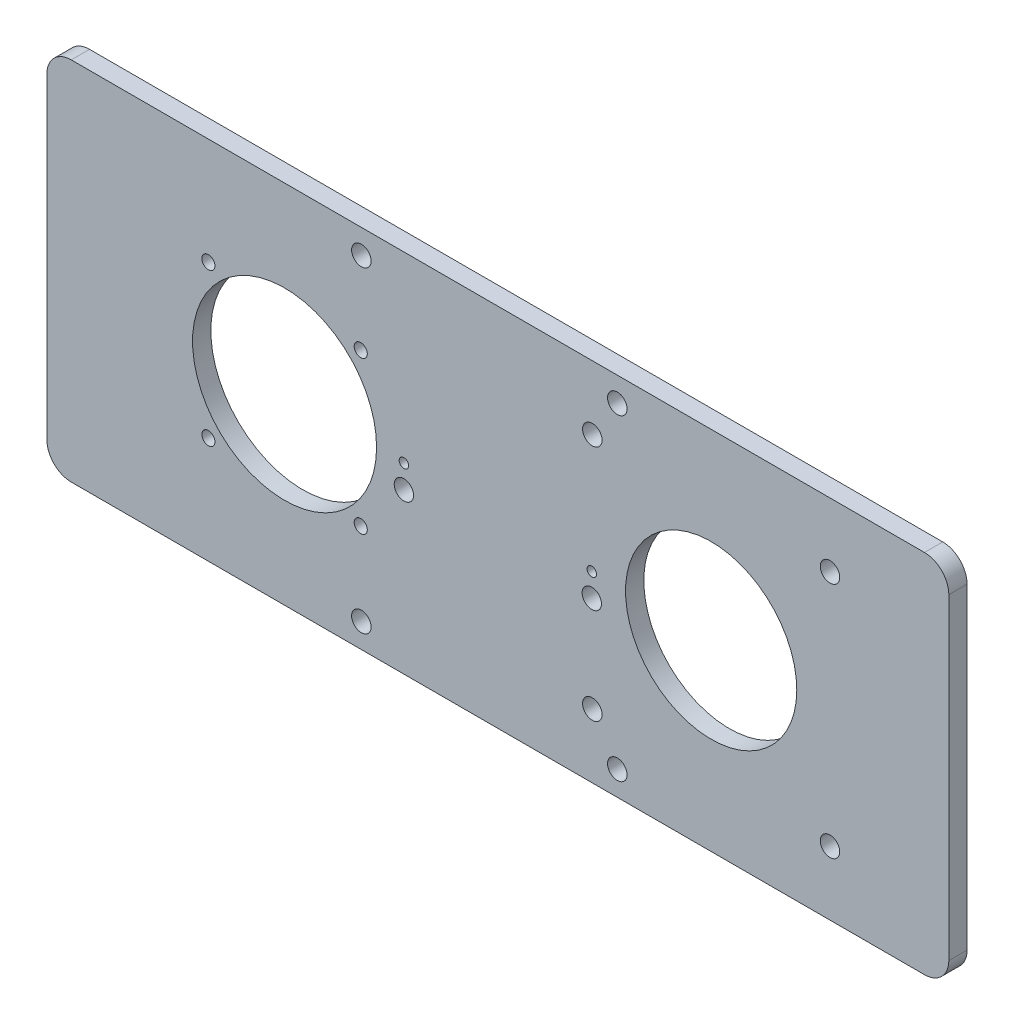
SolidWorks part; units mm, degrees
material "Dragon Plate Carbon Fiber"
ref_plane "Front" through (0, 0, 0) normal (0, 0, 1) x (1, 0, 0)
ref_plane "Top" through (0, 0, 0) normal (0, 1, 0) x (1, 0, 0)
ref_plane "Right" through (0, 0, 0) normal (1, 0, 0) x (0, 0, -1)
sketch "Sketch3" plane through (0, 0, 0) normal (0, 0, 1) x (1, 0, 0)
  line L1 (-74, 30) -> (74, 30)
  line L3 (-74, -30) -> (74, -30) construction
  line L8 (-35, 0) -> (35, 0) construction
  line L23 (-74, 30) -> (-74, -30)
  line L24 (-74, -30) -> (74, -30)
  line L25 (74, -30) -> (74, 30)
  line L27 (-22.4, 26) -> (-22.4, -26) construction
  line L28 (-47.5, -12.5) -> (-22.5, -12.5) construction
  line L29 (-47.5, -12.5) -> (-47.5, 12.5) construction
  line L30 (-47.5, 12.5) -> (-22.5, 12.5) construction
  line L31 (-22.5, -12.5) -> (-22.5, 12.5) construction
  line L32 (-47.5, -12.5) -> (-22.5, 12.5) construction
  line L33 (-47.5, 12.5) -> (-22.5, -12.5) construction
  line L34 (15.5, -19.5) -> (54.5, -19.5) construction
  line L35 (15.5, -19.5) -> (15.5, 19.5) construction
  line L36 (15.5, 19.5) -> (54.5, 19.5) construction
  line L37 (54.5, -19.5) -> (54.5, 19.5) construction
  line L38 (15.5, -19.5) -> (54.5, 19.5) construction
  line L39 (15.5, 19.5) -> (54.5, -19.5) construction
  line L44 (-22.4, -26) -> (19.6, -26) construction
  line L45 (19.6, -26) -> (19.6, 26) construction
  line L50 (19.6, 26) -> (-22.4, 26) construction
  line L65 (15.4159, 0) -> (15.4159, -3.81) construction
  line L67 (-15.42, 0) -> (-15.42, -3.81) construction
  circle A0 centre (-35, 0) radius 15.1
  circle A1 centre (35, 0) radius 14.05
  point P1 (-74, 0)
  dimension "D8" = 30.2
  dimension "D12" = 28.1
  dimension "D7" = 25
  dimension "D9" = 30.8359
  dimension "D5" = 60
  dimension "D13" = 148
  dimension "D14" = 148
  dimension "D15" = 148
  dimension "D6" = 3.81
  dimension "D11" = 15.42
  dimension "D16" = 39
  dimension "D17" = 74
  dimension "D21" = 42
  dimension "D22" = 22.4
  dimension "D19" = 52
  dimension "D20" = 26
  dimension "D3" = 70
  dimension "D4" = 35
extrude "Boss-Extrude2" add sketch "Sketch3" against normal blind 3
fillet "Fillet1" radius 4 4 edges at (-74, -30, -1.5) (74, -30, -1.5) (-74, 30, -1.5) (74, 30, -1.5)
sketch "Sketch4" plane through (0, 0, 0) normal (0, 0, 1) x (1, 0, 0)
  point P4 (-47.5, 12.5)
  point P6 (-22.5, 12.5)
  point P8 (-22.5, -12.5)
  point P10 (-47.5, -12.5)
hole_wizard "EVK4-Holes" positions "Sketch4" profile "Sketch6" hole size "Ø1.0" standard "ISO" end condition through all
sketch "Sketch6" plane through (-47.5, 12.5, 0) normal (1, 0, 0) x (0, -1, 0)
  line L0 (0, 0) -> (0, 3)
  line L1 (0, 3) -> (1.075, 3)
  line L2 (1.075, 3) -> (1.075, 0)
  line L5 (1.075, 0) -> (0, 0)
  line L11 (0, -6.35) -> (0, 107.95) construction
  dimension "Thru Hole Dia." = 2.15
  dimension "Thru Hole Depth" = 3
sketch "Sketch7" plane through (0, 0, 0) normal (0, 0, 1) x (1, 0, 0)
  point P0 (15.5, 19.5)
  point P1 (54.5, 19.5)
  point P3 (54.5, -19.5)
  point P5 (15.5, -19.5)
hole_wizard "FLIR-Holes" positions "Sketch7" profile "Sketch8" hole size "Ø1.0" standard "ISO" end condition through all
sketch "Sketch8" plane through (15.5, 19.5, 0) normal (1, 0, 0) x (0, -1, 0)
  line L0 (0, 0) -> (0, 3)
  line L1 (0, 3) -> (1.6, 3)
  line L2 (1.6, 3) -> (1.6, 0)
  line L5 (1.6, 0) -> (0, 0)
  line L11 (0, -6.35) -> (0, 107.95) construction
  dimension "Thru Hole Dia." = 3.2
  dimension "Thru Hole Depth" = 3
sketch "Sketch9" plane through (0, 0, 0) normal (0, 0, 1) x (1, 0, 0)
  point P0 (-15.42, -3.81)
  point P1 (15.4159, -3.81)
hole_wizard "VN-Mount-Holes" positions "Sketch9" profile "Sketch10" hole size "Ø1.0" standard "ISO" end condition through all
sketch "Sketch10" plane through (-15.42, -3.81, 0) normal (1, 0, 0) x (0, -1, 0)
  line L0 (0, 0) -> (0, 3)
  line L1 (0, 3) -> (1.5875, 3)
  line L2 (1.5875, 3) -> (1.5875, 0)
  line L5 (1.5875, 0) -> (0, 0)
  line L11 (0, -6.35) -> (0, 107.95) construction
  dimension "Thru Hole Dia." = 3.175
  dimension "Thru Hole Depth" = 3
sketch "Sketch11" plane through (0, 0, 0) normal (0, 0, 1) x (1, 0, 0)
  point P0 (-15.42, 0)
  point P1 (15.4159, 0)
hole_wizard "VN-Ref-Holes" positions "Sketch11" profile "Sketch12" hole size "Ø1.0" standard "ISO" end condition through all
sketch "Sketch12" plane through (-15.42, 0, 0) normal (1, 0, 0) x (0, -1, 0)
  line L0 (0, 0) -> (0, 3)
  line L1 (0, 3) -> (0.775, 3)
  line L2 (0.775, 3) -> (0.775, 0)
  line L5 (0.775, 0) -> (0, 0)
  line L11 (0, -6.35) -> (0, 107.95) construction
  dimension "Thru Hole Dia." = 1.55
  dimension "Thru Hole Depth" = 3
sketch "Sketch13" plane through (0, 0, 0) normal (0, 0, 1) x (1, 0, 0)
  point P0 (-22.4, 26)
  point P1 (19.6, 26)
  point P3 (19.6, -26)
  point P5 (-22.4, -26)
hole_wizard "PCB-Mount-Holes" positions "Sketch13" profile "Sketch14" hole size "Ø1.0" standard "ISO" end condition through all
sketch "Sketch14" plane through (-22.4, 26, 0) normal (1, 0, 0) x (0, -1, 0)
  line L0 (0, 0) -> (0, 3)
  line L1 (0, 3) -> (1.6, 3)
  line L2 (1.6, 3) -> (1.6, 0)
  line L5 (1.6, 0) -> (0, 0)
  line L11 (0, -6.35) -> (0, 107.95) construction
  dimension "Thru Hole Dia." = 3.2
  dimension "Thru Hole Depth" = 3
equation "\"M3 Press Fit Nut Diameter\"= 4.22mm"
equation "\"M3 Clearance\"= 3.15mm"
equation "\"CF Thickness\"= 3mm"
equation "\"Tab Clearance\"= 0.1mm"
equation "\"Tab Width\"= 6mm"
equation "\"D11@Sketch3\"=30.84/2"
equation "\"D1@Boss-Extrude2\"=\"CF Thickness\""
equation "\"Plate Width\"= 148mm"
equation "\"Plate Height\"= 60mm"
equation "\"D15@Sketch3\"=\"Plate Width\""
equation "\"PCB Width\"= 42mm"
equation "\"PCB Height\"= 52mm"
equation "\"D17@Sketch3\"=\"Plate Width\"/2"
equation "\"D21@Sketch3\"=\"PCB Width\""
equation "\"D22@Sketch3\"=\"PCB Width\"/2+1.4"
equation "\"D5@Sketch3\"=\"Plate Height\""
equation "\"D19@Sketch3\"=\"PCB Height\""
equation "\"D20@Sketch3\"=\"PCB Height\"/2"
equation "\"Camera Spacing\"= 70mm"
equation "\"D3@Sketch3\"=\"Camera Spacing\""
equation "\"D4@Sketch3\"=\"Camera Spacing\"/2"
